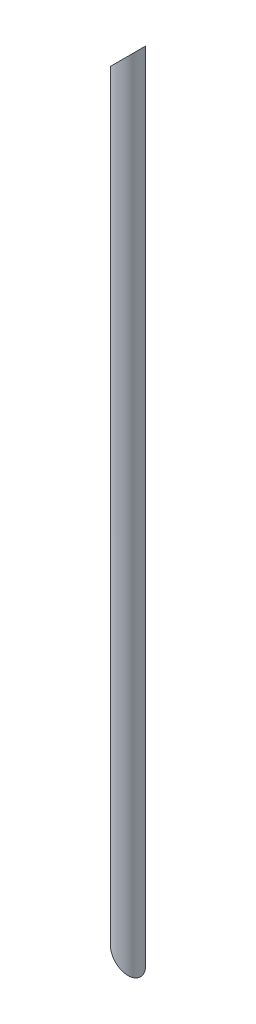
SolidWorks part; units mm, degrees
ref_plane "Plano frontal" through (0, 0, 0) normal (0, 0, 1) x (1, 0, 0)
ref_plane "Plano superior" through (0, 0, 0) normal (0, 1, 0) x (1, 0, 0)
ref_plane "Plano direito" through (0, 0, 0) normal (1, 0, 0) x (0, 0, -1)
sketch "Esboço2" plane through (0, 0, 0) normal (0, 0, 1) x (1, 0, 0)
  line L0 (0, 0) -> (0, 2530.71) construction
  line L1 (39.3, 0) -> (39.3, 2530.71)
  line L2 (39.3, 2530.71) -> (0, 2530.71)
  line L3 (39.3, 0) -> (0, 0)
  line L4 (0, 0) -> (0, 2530.71)
  dimension "D1" = 39.3
  dimension "D2" = 2530.71
revolve "Revolução2" add sketch "Esboço2" angle 360 about L0
sketch "Esboço3" plane through (0, 0, 0) normal (0, 0, 1) x (1, 0, 0)
  line L0 (-39.3, 2530.71) -> (39.3, 2530.71)
  line L1 (39.3, 2530.71) -> (-39.3, 2452.11)
  line L2 (-39.3, 2530.71) -> (-39.3, 0) construction
  line L3 (-39.3, 2452.11) -> (-39.3, 2530.71)
  line L4 (39.3, 0) -> (-39.3, 78.6)
  line L8 (-39.3, 78.6) -> (-39.3, 0)
  line L9 (-39.3, 0) -> (39.3, 0)
extrude "Corte-extrusão1" cut sketch "Esboço3" against normal through all both and the other way through all
sketch "Esboço9" plane through (0, 0, 0) normal (0, 1, 0) x (1, 0, 0)
  circle A0 centre (0, 0) radius 35.8738
extrude "Corte-extrusão6" cut sketch "Esboço9" along normal through all
